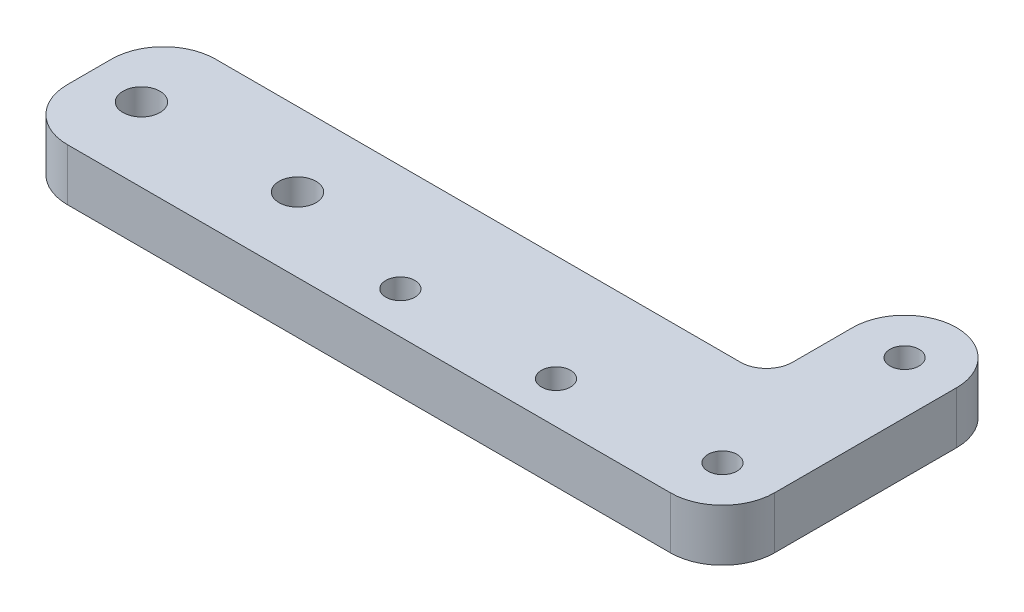
SolidWorks part; units mm, degrees
ref_plane "Front Plane" through (0, 0, 0) normal (0, 0, 1) x (1, 0, 0)
ref_plane "Top Plane" through (0, 0, 0) normal (0, 1, 0) x (1, 0, 0)
ref_plane "Right Plane" through (0, 0, 0) normal (1, 0, 0) x (0, 0, -1)
sketch "Sketch1" plane through (0, 0, 0) normal (0, 1, 0) x (1, 0, 0)
  line L0 (14.2331, 5.816) -> (14.2331, -5.2965)
  line L1 (-25.7469, 0.5685) -> (6.2956, 0.5685)
  line L2 (-28.9219, -2.6065) -> (-28.9219, -5.2965)
  line L3 (-25.7469, -8.4715) -> (11.0581, -8.4715)
  line L4 (7.8831, 5.816) -> (7.8831, 2.156)
  circle A0 centre (-7.9669, -5.9315) radius 0.889
  circle A1 centre (1.5331, -5.9315) radius 0.889
  circle A2 centre (11.0581, 5.816) radius 0.889
  arc A3 (14.2331, -5.2965) -> (11.0581, -8.4715) centre (11.0581, -5.2965) cw
  circle A4 centre (-25.7469, -3.9515) radius 1.1303
  circle A5 centre (-16.2219, -3.9515) radius 1.1303
  arc A6 (14.2331, 5.816) -> (7.8831, 5.816) centre (11.0581, 5.816) ccw
  arc A7 (-25.7469, 0.5685) -> (-28.9219, -2.6065) centre (-25.7469, -2.6065) ccw
  arc A8 (-28.9219, -5.2965) -> (-25.7469, -8.4715) centre (-25.7469, -5.2965) ccw
  arc A9 (7.8831, 2.156) -> (6.2956, 0.5685) centre (6.2956, 2.156) cw
  circle A10 centre (11.0581, -5.2965) radius 0.889
  dimension "D1" = 1.778
  dimension "D2" = 1.778
  dimension "D3" = 9.5
  dimension "D4" = 0
  dimension "D5" = 6.5
  dimension "D6" = 6.5
  dimension "D7" = 2.54
  dimension "D8" = 20.955
  dimension "D9" = 1.5875
  dimension "D10" = 1.778
  dimension "D11" = 3.175
  dimension "D12" = 14.2875
  dimension "D13" = 3.175
  dimension "D14" = 2.2606
  dimension "D15" = 2.2606
  dimension "D16" = 9.525
  dimension "D17" = 3.175
  dimension "D18" = 3.175
  dimension "D19" = 27.28
  dimension "D20" = 1.345
  dimension "D21" = 9.04
extrude "Boss-Extrude1" add sketch "Sketch1" along normal blind 3.175
